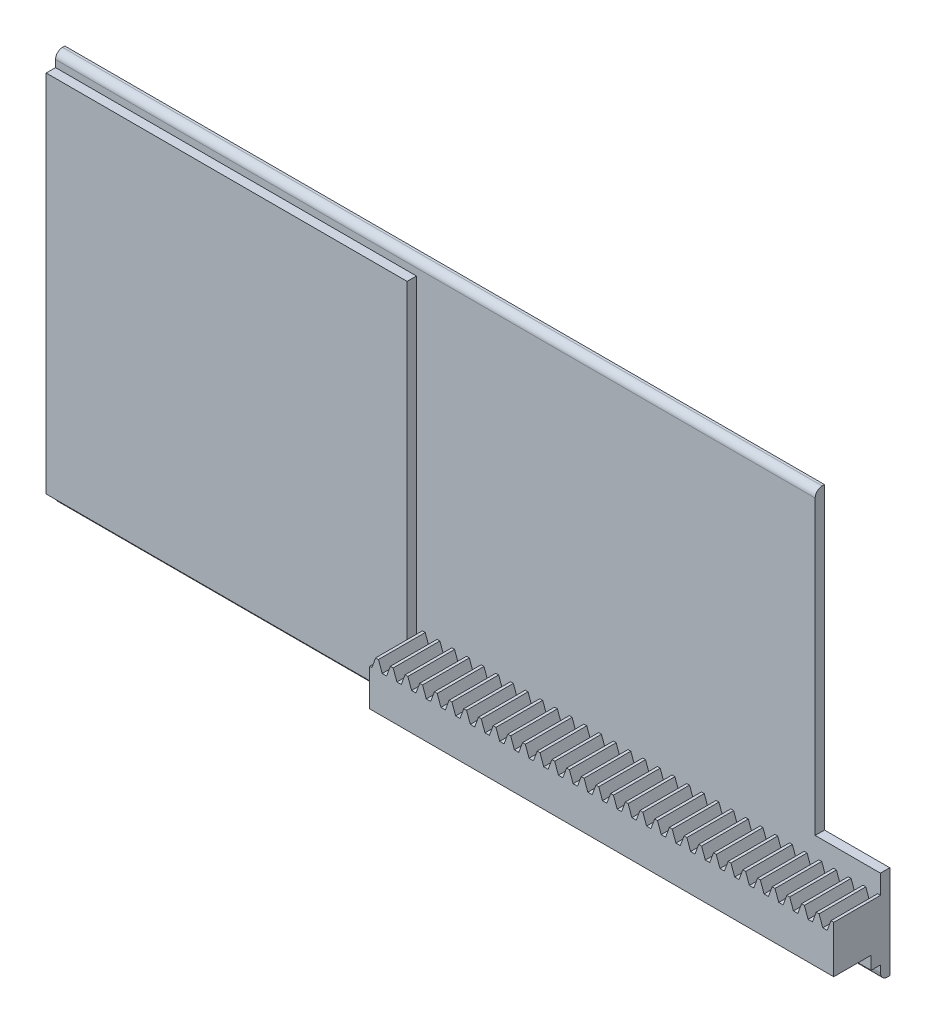
SolidWorks part; units mm, degrees
material "PET"
ref_plane "Front Plane" through (0, 0, 0) normal (0, 0, 1) x (1, 0, 0)
ref_plane "Top Plane" through (0, 0, 0) normal (0, 1, 0) x (1, 0, 0)
ref_plane "Right Plane" through (0, 0, 0) normal (1, 0, 0) x (0, 0, -1)
sketch "Sketch1" plane through (0, 0, 0) normal (0, 0, 1) x (1, 0, 0)
  line L0 (-50.8, 0) -> (-53.975, 0) construction
  line L1 (-53.975, 53.34) -> (152.4, 53.34)
  line L2 (-53.975, 53.34) -> (-53.975, -53.34)
  line L3 (-53.975, -53.34) -> (152.4, -53.34)
  line L4 (152.4, 53.34) -> (152.4, -53.34)
  line L5 (50.8, 0) -> (152.4, 0) construction
  circle A0 centre (0, 0) radius 50.8 construction
  dimension "D1" = 101.6
  dimension "D2" = 3.175
  dimension "D3" = 101.6
  dimension "D4" = 106.68
extrude "Boss-Extrude1" add sketch "Sketch1" along normal blind 2.54 contours L2 L3 L4 L1
sketch "Sketch2" plane through (0, 0, 2.54) normal (0, 0, 1) x (1, 0, 0)
  line L2 (170.1453, -33.159) -> (169.3797, -33.159)
  line L3 (169.3797, -33.159) -> (168.3627, -35.953)
  line L4 (168.3627, -35.953) -> (167.1724, -35.953)
  line L5 (167.1724, -35.953) -> (166.1555, -33.159)
  line L6 (166.1555, -33.159) -> (165.3898, -33.159)
  line L7 (165.3898, -33.159) -> (164.3729, -35.953)
  line L8 (164.3729, -35.953) -> (163.1826, -35.953)
  line L9 (163.1826, -35.953) -> (162.1656, -33.159)
  line L10 (162.1656, -33.159) -> (161.4, -33.159)
  line L11 (161.4, -33.159) -> (160.3831, -35.953)
  line L12 (160.3831, -35.953) -> (159.1928, -35.953)
  line L13 (159.1928, -35.953) -> (158.1758, -33.159)
  line L14 (158.1758, -33.159) -> (157.4102, -33.159)
  line L15 (157.4102, -33.159) -> (156.3933, -35.953)
  line L16 (156.3933, -35.953) -> (155.2029, -35.953)
  line L17 (155.2029, -35.953) -> (154.186, -33.159)
  line L18 (154.186, -33.159) -> (153.4204, -33.159)
  line L19 (153.4204, -33.159) -> (152.4034, -35.953)
  line L20 (152.4034, -35.953) -> (151.2131, -35.953)
  line L21 (151.2131, -35.953) -> (150.1962, -33.159)
  line L22 (150.1962, -33.159) -> (149.4305, -33.159)
  line L23 (149.4305, -33.159) -> (148.4136, -35.953)
  line L24 (148.4136, -35.953) -> (147.2233, -35.953)
  line L25 (147.2233, -35.953) -> (146.2064, -33.159)
  line L26 (146.2064, -33.159) -> (145.4407, -33.159)
  line L27 (145.4407, -33.159) -> (144.4238, -35.953)
  line L28 (144.4238, -35.953) -> (143.2335, -35.953)
  line L29 (143.2335, -35.953) -> (142.2165, -33.159)
  line L30 (142.2165, -33.159) -> (141.4509, -33.159)
  line L31 (141.4509, -33.159) -> (140.434, -35.953)
  line L32 (140.434, -35.953) -> (139.2436, -35.953)
  line L33 (139.2436, -35.953) -> (138.2267, -33.159)
  line L34 (138.2267, -33.159) -> (137.4611, -33.159)
  line L35 (137.4611, -33.159) -> (136.4441, -35.953)
  line L36 (136.4441, -35.953) -> (135.2538, -35.953)
  line L37 (135.2538, -35.953) -> (134.2369, -33.159)
  line L38 (134.2369, -33.159) -> (133.4713, -33.159)
  line L39 (133.4713, -33.159) -> (132.4543, -35.953)
  line L40 (132.4543, -35.953) -> (131.264, -35.953)
  line L41 (131.264, -35.953) -> (130.2471, -33.159)
  line L42 (130.2471, -33.159) -> (129.4814, -33.159)
  line L43 (129.4814, -33.159) -> (128.4645, -35.953)
  line L44 (128.4645, -35.953) -> (127.2742, -35.953)
  line L45 (127.2742, -35.953) -> (126.2572, -33.159)
  line L46 (126.2572, -33.159) -> (125.4916, -33.159)
  line L47 (125.4916, -33.159) -> (124.4747, -35.953)
  line L48 (124.4747, -35.953) -> (123.2843, -35.953)
  line L49 (123.2843, -35.953) -> (122.2674, -33.159)
  line L50 (122.2674, -33.159) -> (121.5018, -33.159)
  line L51 (121.5018, -33.159) -> (120.4849, -35.953)
  line L52 (120.4849, -35.953) -> (119.2945, -35.953)
  line L53 (119.2945, -35.953) -> (118.2776, -33.159)
  line L54 (118.2776, -33.159) -> (117.512, -33.159)
  line L55 (117.512, -33.159) -> (116.495, -35.953)
  line L56 (116.495, -35.953) -> (115.3047, -35.953)
  line L57 (115.3047, -35.953) -> (114.2878, -33.159)
  line L58 (114.2878, -33.159) -> (113.5221, -33.159)
  line L59 (113.5221, -33.159) -> (112.5052, -35.953)
  line L60 (112.5052, -35.953) -> (111.3149, -35.953)
  line L61 (111.3149, -35.953) -> (110.2979, -33.159)
  line L62 (110.2979, -33.159) -> (109.5323, -33.159)
  line L63 (109.5323, -33.159) -> (108.5154, -35.953)
  line L64 (108.5154, -35.953) -> (107.3251, -35.953)
  line L65 (107.3251, -35.953) -> (106.3081, -33.159)
  line L66 (106.3081, -33.159) -> (105.5425, -33.159)
  line L67 (105.5425, -33.159) -> (104.5256, -35.953)
  line L68 (104.5256, -35.953) -> (103.3352, -35.953)
  line L69 (103.3352, -35.953) -> (102.3183, -33.159)
  line L70 (102.3183, -33.159) -> (101.5527, -33.159)
  line L71 (101.5527, -33.159) -> (100.5357, -35.953)
  line L72 (100.5357, -35.953) -> (99.3454, -35.953)
  line L73 (99.3454, -35.953) -> (98.3285, -33.159)
  line L74 (98.3285, -33.159) -> (97.5629, -33.159)
  line L75 (97.5629, -33.159) -> (96.5459, -35.953)
  line L76 (96.5459, -35.953) -> (95.3556, -35.953)
  line L77 (95.3556, -35.953) -> (94.3387, -33.159)
  line L78 (94.3387, -33.159) -> (93.573, -33.159)
  line L79 (93.573, -33.159) -> (92.5561, -35.953)
  line L80 (92.5561, -35.953) -> (91.3658, -35.953)
  line L81 (91.3658, -35.953) -> (90.3488, -33.159)
  line L82 (90.3488, -33.159) -> (89.5832, -33.159)
  line L83 (89.5832, -33.159) -> (88.5663, -35.953)
  line L84 (88.5663, -35.953) -> (87.3759, -35.953)
  line L85 (87.3759, -35.953) -> (86.359, -33.159)
  line L86 (86.359, -33.159) -> (85.5934, -33.159)
  line L87 (85.5934, -33.159) -> (84.5765, -35.953)
  line L88 (84.5765, -35.953) -> (83.3861, -35.953)
  line L89 (83.3861, -35.953) -> (82.3692, -33.159)
  line L90 (82.3692, -33.159) -> (81.6036, -33.159)
  line L91 (81.6036, -33.159) -> (80.5866, -35.953)
  line L92 (80.5866, -35.953) -> (79.3963, -35.953)
  line L93 (79.3963, -35.953) -> (78.3794, -33.159)
  line L94 (78.3794, -33.159) -> (77.6137, -33.159)
  line L95 (77.6137, -33.159) -> (76.5968, -35.953)
  line L96 (76.5968, -35.953) -> (75.4065, -35.953)
  line L97 (75.4065, -35.953) -> (74.3895, -33.159)
  line L98 (74.3895, -33.159) -> (73.6239, -33.159)
  line L99 (73.6239, -33.159) -> (72.607, -35.953)
  line L100 (72.607, -35.953) -> (71.4167, -35.953)
  line L101 (71.4167, -35.953) -> (70.3997, -33.159)
  line L102 (70.3997, -33.159) -> (69.6341, -33.159)
  line L103 (69.6341, -33.159) -> (68.6172, -35.953)
  line L104 (68.6172, -35.953) -> (67.4268, -35.953)
  line L105 (67.4268, -35.953) -> (66.4099, -33.159)
  line L106 (66.4099, -33.159) -> (65.6443, -33.159)
  line L107 (65.6443, -33.159) -> (64.6273, -35.953)
  line L108 (64.6273, -35.953) -> (63.437, -35.953)
  line L109 (63.437, -35.953) -> (62.4201, -33.159)
  line L110 (62.4201, -33.159) -> (61.6544, -33.159)
  line L111 (61.6544, -33.159) -> (60.6375, -35.953)
  line L112 (60.6375, -35.953) -> (59.4472, -35.953)
  line L113 (59.4472, -35.953) -> (58.4303, -33.159)
  line L114 (58.4303, -33.159) -> (57.6646, -33.159)
  line L115 (57.6646, -33.159) -> (56.6477, -35.953)
  line L116 (56.6477, -35.953) -> (55.4574, -35.953)
  line L117 (55.4574, -35.953) -> (54.4404, -33.159)
  line L118 (54.4404, -33.159) -> (53.6748, -33.159)
  line L119 (53.6748, -33.159) -> (52.6579, -35.953)
  line L120 (52.6579, -35.953) -> (51.4675, -35.953)
  line L121 (51.4675, -35.953) -> (50.4506, -33.159)
  line L122 (50.4506, -33.159) -> (49.685, -33.159)
  line L123 (49.685, -33.159) -> (48.668, -35.953)
  line L124 (48.668, -35.953) -> (47.4777, -35.953)
  line L125 (47.4777, -35.953) -> (46.4608, -33.159)
  line L126 (46.4608, -33.159) -> (45.6952, -33.159)
  line L127 (45.6952, -33.159) -> (44.6782, -35.953)
  line L128 (44.6782, -35.953) -> (44.0831, -35.953)
  line L131 (44.0831, -35.953) -> (44.0831, -45.9799)
  line L132 (44.0831, -45.9799) -> (170.1453, -45.9799)
  line L133 (170.1453, -45.9799) -> (170.1453, -33.159)
extrude "Boss-Extrude2" add sketch "Sketch2" along normal blind 12.7 contours L2 L3 L4 L5 L6 L7 L8 L9 L10 L11 L12 L13 L14 L15 L16 L17 L18 L19 L20 L21 L22 L23 L24 L25 L26 L27 L28 L29 L30 L31 L32 L33 L34 L35 L36 L37 L38 L39 L40 L41 L42 L43 L44 L45 L46 L47 L48 L49 L50 L51 L52 L53 L54 L55 L56 L57 L58 L59 L60 L61 L62 L63 L64 L65 L66 L67 L68 L69 L70 L71 L72 L73 L74 L75 L76 L77 L78 L79 L80 L81 L82 L83 L84 L85 L86 L87 L88 L89 L90 L91 L92 L93 L94 L95 L96 L97 L98 L99 L100 L101 L102 L103 L104 L105 L106 L107 L108 L109 L110 L111 L112 L113 L114 L115 L116 L117 L118 L119 L120 L121 L122 L123 L124 L125 L126 L127 L128 L131 L132 L133
sketch "Sketch3" plane through (0, 0, 0) normal (0, 0, -1) x (-1, 0, 0)
  line L0 (-152.4, 53.34) -> (-152.4, -53.34) construction
  line L1 (-170.1453, -53.34) -> (-152.4, -53.34)
  line L2 (-170.1453, -53.34) -> (-170.1453, -27.94)
  line L3 (-170.1453, -27.94) -> (-152.4, -27.94)
  line L4 (-152.4, -53.34) -> (-152.4, -27.94)
  line L5 (-170.1453, -45.9799) -> (-170.1453, -33.159) construction
  dimension "D1" = 25.4
extrude "Boss-Extrude3" add sketch "Sketch3" against normal up to surface (2.54 mm away) up to face at (96.2754, -33.5855, 2.54)
fillet "Fillet1" radius 1.905 2 edges at (58.0851, -53.34, 2.54) (49.2125, 53.34, 2.54)
sketch "Sketch5" plane through (0, 0, 2.54) normal (0, 0, 1) x (1, 0, 0)
  line L0 (-53.975, 51.435) -> (-53.975, -51.435) construction
  line L1 (-53.975, 49.53) -> (44.0831, 49.53)
  line L2 (-53.975, 49.53) -> (-53.975, -49.53)
  line L3 (-53.975, -49.53) -> (44.0831, -49.53)
  line L4 (44.0831, 49.53) -> (44.0831, -45.9799)
  line L6 (-53.975, 53.34) -> (152.4, 53.34) construction
  line L7 (170.1453, -53.34) -> (-53.975, -53.34) construction
  line L8 (44.0831, -35.953) -> (44.0831, -45.9799) construction
  line L9 (44.0831, -45.9799) -> (170.1453, -45.9799)
  line L10 (170.1453, -45.9799) -> (170.1453, -49.53)
  line L11 (170.1453, -51.435) -> (170.1453, -45.9799) construction
  line L12 (170.1453, -49.53) -> (44.0831, -49.53)
  dimension "D1" = 3.81
  dimension "D2" = 3.81
extrude "Boss-Extrude4" add sketch "Sketch5" along normal blind 2.54
sketch "Sketch6" plane through (0, 0, 0) normal (0, 0, -1) x (-1, 0, 0)
  circle A0 centre (0, 0) radius 38.1
  dimension "D1" = 76.2
extrude "Cut-Extrude1" cut sketch "Sketch6" against normal blind 1.5875
